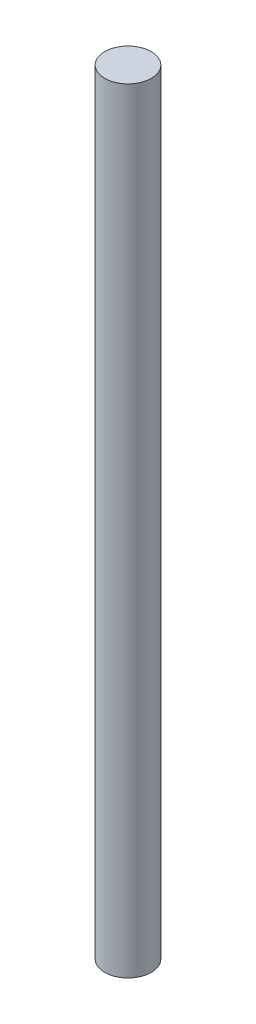
SolidWorks part; units mm, degrees
ref_plane "前视基准面" through (0, 0, 0) normal (0, 0, 1) x (1, 0, 0)
ref_plane "上视基准面" through (0, 0, 0) normal (0, 1, 0) x (1, 0, 0)
ref_plane "右视基准面" through (0, 0, 0) normal (1, 0, 0) x (0, 0, -1)
other "Configuration Table"
sketch "草图1" plane through (0, 0, 0) normal (0, 1, 0) x (1, 0, 0)
  circle A0 centre (0, 0) radius 2.1
  dimension "D1" = 4.2
extrude "凸台-拉伸1" add sketch "草图1" along normal blind 70
